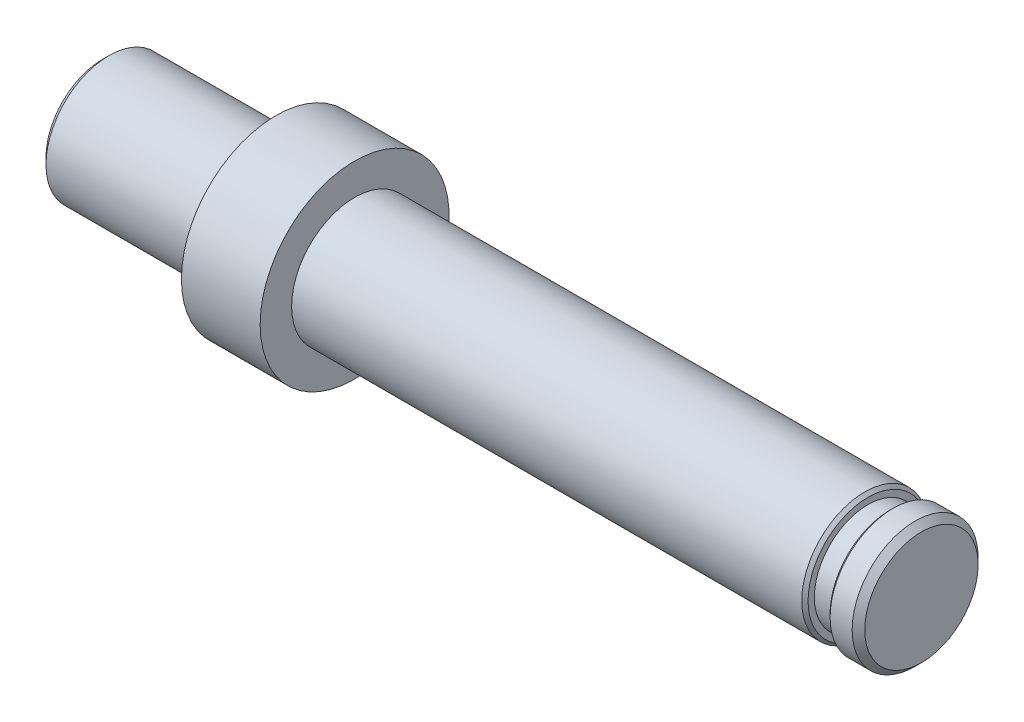
SolidWorks part; units mm, degrees
ref_plane "Спереди" through (0, 0, 0) normal (0, 0, 1) x (1, 0, 0)
ref_plane "Сверху" through (0, 0, 0) normal (0, 1, 0) x (1, 0, 0)
ref_plane "Справа" through (0, 0, 0) normal (1, 0, 0) x (0, 0, -1)
sketch "Эскиз1" plane through (0, 0, 0) normal (0, 0, 1) x (1, 0, 0)
  line L0 (0, 0) -> (26, 0)
  line L1 (26, 0) -> (26, 2)
  line L2 (26, 2) -> (25, 2)
  line L3 (25, 2) -> (25, 1.7)
  line L4 (25, 1.7) -> (24.3, 1.7)
  line L5 (24.3, 1.7) -> (24.3, 2)
  line L6 (24.3, 2) -> (8, 2)
  line L7 (8, 2) -> (8, 3)
  line L8 (8, 3) -> (5.5, 3)
  line L9 (5.5, 3) -> (5.5, 2)
  line L10 (5.5, 2) -> (0, 2)
  line L11 (0, 2) -> (0, 0)
  dimension "D1" = 2
  dimension "D2" = 5.5
  dimension "D3" = 3
  dimension "D4" = 1
  dimension "D5" = 2
  dimension "D6" = 2
  dimension "D7" = 26
  dimension "D8" = 1
  dimension "D9" = 0.7
  dimension "D10" = 1.7
  dimension "D11" = 2.5
revolve "Повернуть1" add sketch "Эскиз1" angle 360 about L0
chamfer "Фаска1" distance 0.2 angle 45 2 edges at (0, 0, 2) (26, 0, 2)
chamfer "Фаска2" distance 0.1 angle 45 2 edges at (25, 0, 2) (24.3, 0, 2)
